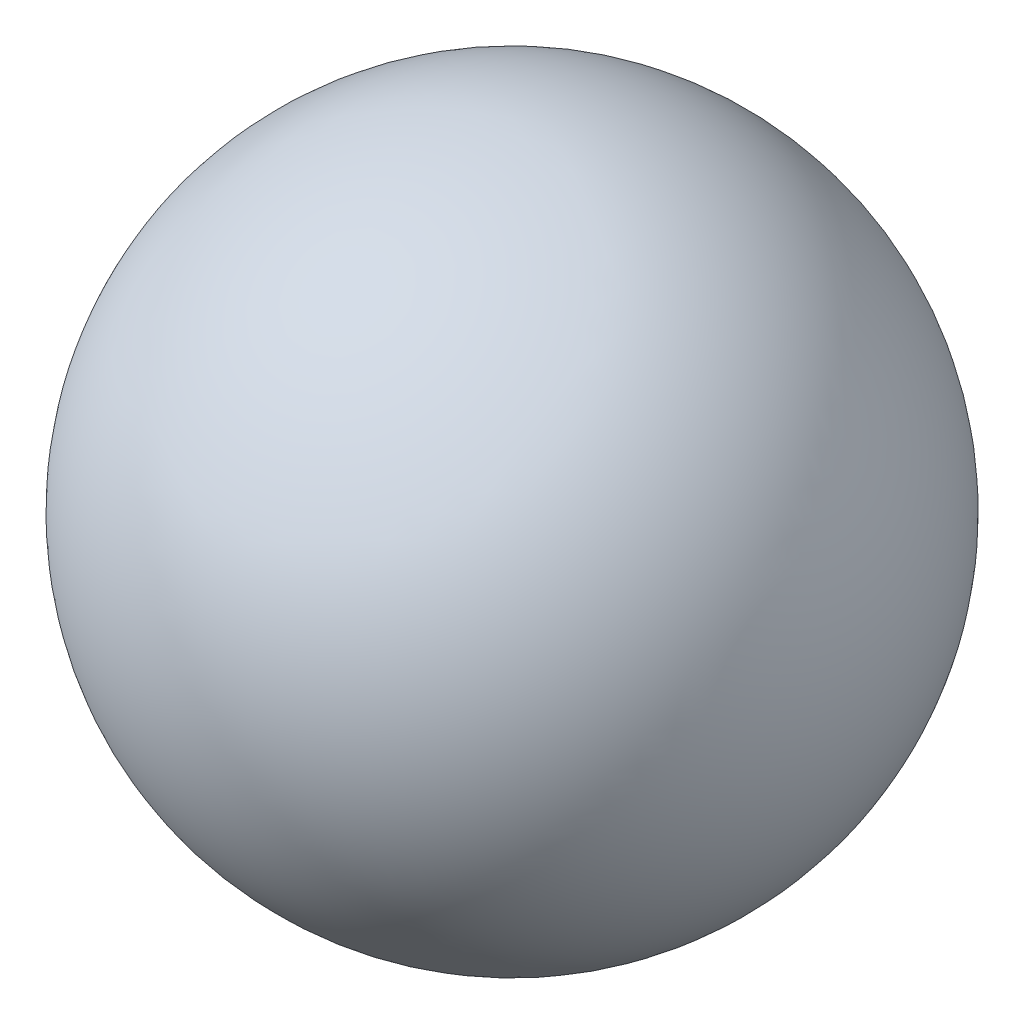
SolidWorks part; units mm, degrees
ref_plane "Спереди" through (0, 0, 0) normal (0, 0, 1) x (1, 0, 0)
ref_plane "Сверху" through (0, 0, 0) normal (0, 1, 0) x (1, 0, 0)
ref_plane "Справа" through (0, 0, 0) normal (1, 0, 0) x (0, 0, -1)
sketch "Эскиз1" plane through (0, 0, 0) normal (0, 1, 0) x (1, 0, 0)
  line L0 (-15.7502, 0) -> (20.5716, 0) construction
  line L1 (-5.8886, 0) -> (12.4114, 0)
  arc A0 (-5.8886, 0) -> (12.4114, 0) centre (3.2614, 0) cw
revolve "Повернуть4" add sketch "Эскиз1" angle 360 about L0
